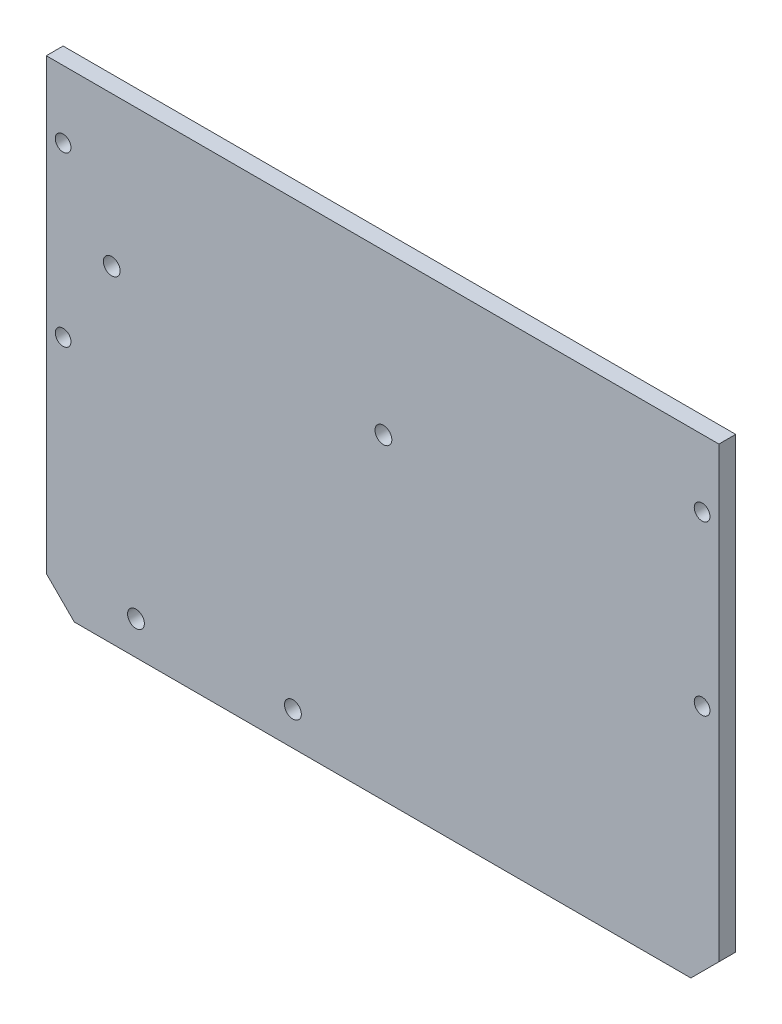
SolidWorks part; units mm, degrees
ref_plane "前视基准面" through (0, 0, 0) normal (0, 0, 1) x (1, 0, 0)
ref_plane "上视基准面" through (0, 0, 0) normal (0, 1, 0) x (1, 0, 0)
ref_plane "右视基准面" through (0, 0, 0) normal (1, 0, 0) x (0, 0, -1)
sketch "草图1" plane through (0, 0, 0) normal (0, 0, 1) x (1, 0, 0)
  line L1 (-60, 42.5) -> (60, 42.5)
  line L2 (-60, 42.5) -> (-60, -42.5)
  line L3 (-60, -42.5) -> (60, -42.5)
  line L4 (60, 42.5) -> (60, -42.5)
  line L5 (-60, 42.5) -> (60, -42.5) construction
  line L6 (-60, -42.5) -> (60, 42.5) construction
  point P0 (0, 0)
  dimension "D1" = 120
  dimension "D2" = 85
extrude "凸台-拉伸1" add sketch "草图1" along normal blind 3
sketch "草图2" plane through (0, 0, 3) normal (0, 0, 1) x (1, 0, 0)
  line L0 (0, 42.5) -> (0, -42.5) construction
  line L1 (60, 42.5) -> (-60, 42.5) construction
  line L2 (-60, -42.5) -> (60, -42.5) construction
  line L3 (-60, 42.5) -> (-60, -42.5) construction
  line L4 (-57, 30.5) -> (-57, 0.5) construction
  circle A0 centre (-57, 30.5) radius 1.4
  circle A1 centre (-57, 0.5) radius 1.4
  circle A2 centre (57, 30.5) radius 1.4
  circle A3 centre (57, 0.5) radius 1.4
  dimension "D1" = 3
  dimension "D2" = 12
  dimension "D3" = 30
  dimension "D4" = 2.8
  dimension "D5" = 2.8
extrude "切除-拉伸1" cut sketch "草图2" against normal through all
sketch "草图3" plane through (0, 0, 3) normal (0, 0, 1) x (1, 0, 0)
  line L0 (-44, -36.5) -> (-16, -36.5) construction
  line L1 (-60, -42.5) -> (60, -42.5) construction
  line L2 (-60, 42.5) -> (-60, -42.5) construction
  circle A0 centre (-44, -36.5) radius 1.5
  circle A1 centre (-16, -36.5) radius 1.5
  circle A2 centre (-48.3214, 15.8218) radius 1.5
  circle A3 centre (0.1436, 13.9815) radius 1.5
  dimension "D1" = 3
  dimension "D2" = 3
  dimension "D3" = 3
  dimension "D4" = 3
  dimension "D5" = 52.5
  dimension "D6" = 28
  dimension "D7" = 48.5
  dimension "D8" = 53
  dimension "D9" = 61.5
  dimension "D10" = 6
  dimension "D11" = 16
extrude "切除-拉伸2" cut sketch "草图3" against normal through all
chamfer "倒角1" distance 5 angle 45 2 edges at (60, -42.5, 1.5) (-60, -42.5, 1.5)
